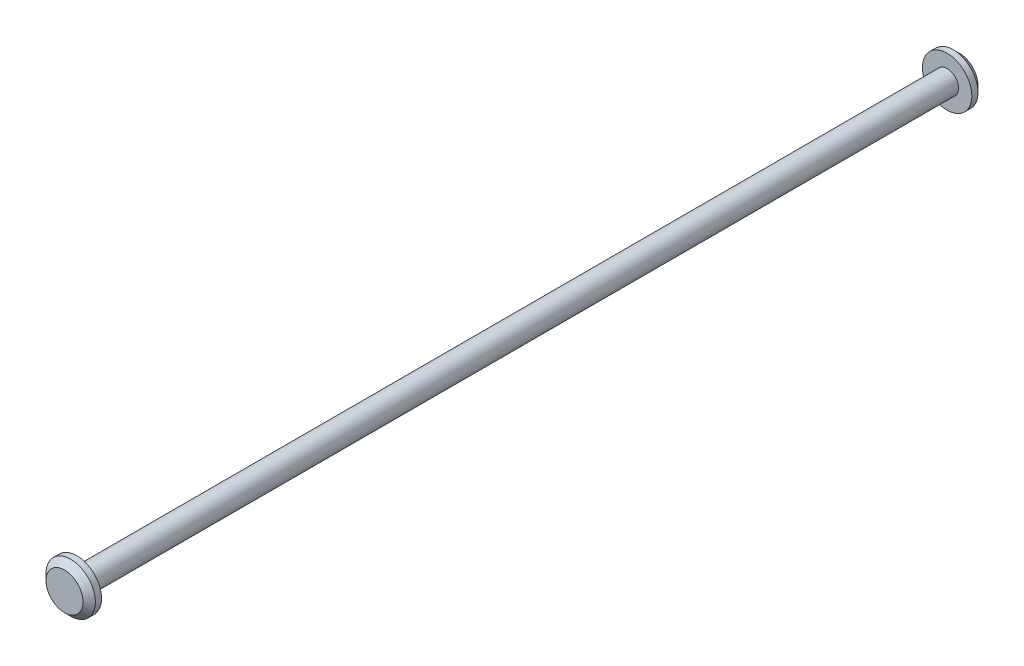
SolidWorks part; units mm, degrees
ref_plane "Front Plane" through (0, 0, 0) normal (0, 0, 1) x (1, 0, 0)
ref_plane "Top Plane" through (0, 0, 0) normal (0, 1, 0) x (1, 0, 0)
ref_plane "Right Plane" through (0, 0, 0) normal (1, 0, 0) x (0, 0, -1)
sketch "Sketch1" plane through (0, 0, 0) normal (0, 0, 1) x (1, 0, 0)
  circle A0 centre (0, 0) radius 0.925
  dimension "D1" = 1.85
extrude "Boss-Extrude1" add sketch "Sketch1" along normal blind 35.25
sketch "Sketch2" plane through (0, 0, 35.25) normal (0, 0, 1) x (1, 0, 0)
  circle A0 centre (0, 0) radius 2
  dimension "D1" = 4
extrude "Boss-Extrude2" add sketch "Sketch2" along normal blind 1
chamfer "Chamfer1" distance 0.5 angle 45 1 edges at (2, 0, 36.25)
mirror "Mirror1" about plane through (0, 0, 0) normal (0, 0, 1) of bodies 102
